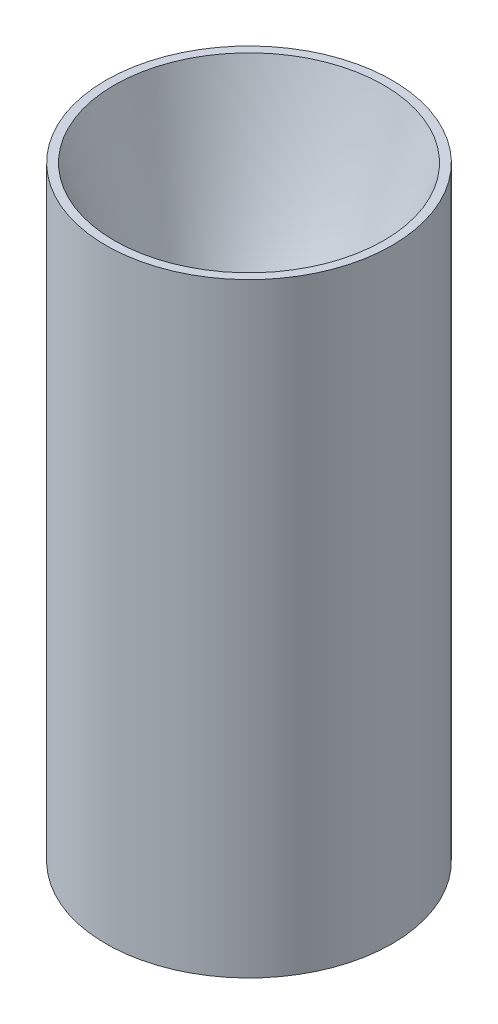
SolidWorks part; units mm, degrees
material "AISI 1020"
ref_plane "Front Plane" through (0, 0, 0) normal (0, 0, 1) x (1, 0, 0)
ref_plane "Top Plane" through (0, 0, 0) normal (0, 1, 0) x (1, 0, 0)
ref_plane "Right Plane" through (0, 0, 0) normal (1, 0, 0) x (0, 0, -1)
sketch "Sketch1" plane through (0, 0, 0) normal (0, 0, 1) x (1, 0, 0)
  line L0 (-0.0055, 165.816) -> (-0.0055, -134.6871) construction
  line L1 (71.7275, 109.9275) -> (76.1945, 109.9275)
  line L4 (53.8815, -59.7275) -> (53.8815, -212.1275)
  line L9 (76.1945, 109.9275) -> (76.1945, -212.1275)
  line L10 (76.1945, -212.1275) -> (53.8815, -212.1275)
  spline S0 degree 2 poles (26.7953, 6.5094) (49.2614, 34.6361) (71.7275, 109.9275) knots 0 0 0 1 1 1 construction
  spline S1 degree 2 poles (26.7953, 6.5094) (49.2614, 34.6361) (71.7275, 109.9275) knots 0 0 0 1 1 1
  spline S2 degree 4 poles (24.1269, -0.7179) (24.126, -0.7018) (24.1243, -0.6738) (24.121, -0.6546) (24.115, -0.5166) (24.1058, -0.4369) (24.0994, -0.1066) (24.0979, 0.0018) (24.102, 0.2678) (24.1085, 0.4272) (24.1205, 0.6469) (24.1414, 0.9016) (24.1752, 1.2027) (24.2265, 1.5422) (24.2905, 1.8812) (24.3671, 2.2165) (24.4563, 2.5494) (24.5577, 2.8783) (24.6716, 3.2035) (24.7972, 3.5238) (24.9353, 3.8398) (25.0841, 4.1494) (25.246, 4.4549) (25.4165, 4.7515) (25.6025, 5.0459) (25.7918, 5.3257) (26.0044, 5.6109) (26.1789, 5.8331) (26.3663, 6.0501) (26.5046, 6.2088) (26.757, 6.4728) (26.837, 6.5526) (27.1016, 6.806) (27.1881, 6.8783) (27.2854, 6.9667) (27.3038, 6.9803) (27.3264, 7.0004) knots 0 0 0 0 0 0.005192 0.010384 0.020768 0.041536 0.082569 0.102427 0.122284 0.142142 0.162 0.201716 0.241431 0.281147 0.320863 0.360578 0.400294 0.44001 0.479725 0.519441 0.559156 0.598872 0.638588 0.678303 0.718019 0.757735 0.79745 0.837166 0.857024 0.876882 0.916597 0.958047 0.979024 0.989512 1 1 1 1 1 construction
  spline S3 degree 4 poles (24.0991, 0.0002) (24.0991, 0.0361) (24.0996, 0.1103) (24.102, 0.2678) (24.1085, 0.4272) (24.1205, 0.6469) (24.1414, 0.9016) (24.1752, 1.2027) (24.2265, 1.5422) (24.2905, 1.8812) (24.3671, 2.2165) (24.4563, 2.5494) (24.5577, 2.8783) (24.6716, 3.2035) (24.7972, 3.5238) (24.9353, 3.8398) (25.0841, 4.1494) (25.246, 4.4549) (25.4165, 4.7515) (25.6025, 5.0459) (25.7918, 5.3257) (26.0044, 5.6109) (26.1789, 5.8331) (26.3663, 6.0501) (26.5046, 6.2088) (26.6704, 6.3823) (26.7445, 6.4586) (26.7953, 6.5094) knots 0.082569 0.082569 0.082569 0.082569 0.082569 0.102427 0.122284 0.142142 0.162 0.201716 0.241431 0.281147 0.320863 0.360578 0.400294 0.44001 0.479725 0.519441 0.559156 0.598872 0.638588 0.678303 0.718019 0.757735 0.79745 0.837166 0.857024 0.876882 0.916597 0.916597 0.916597 0.916597 0.916597
  spline S4 degree 4 poles (24.2082, 2.808) (24.2014, 2.7166) (24.1882, 2.5518) (24.1642, 2.1754) (24.1352, 1.6881) (24.1148, 1.1018) (24.103, 0.6556) (24.0988, 0.1104) (24.0988, -0.0999) (24.102, -0.543) (24.1083, -0.824) (24.1178, -1.1947) (24.1304, -1.5133) (24.1462, -1.8618) (24.1652, -2.1935) (24.1928, -2.6179) (24.2323, -3.1219) (24.3033, -3.8798) (24.4231, -4.8863) (24.5995, -6.0566) (24.8509, -7.385) (25.1518, -8.7034) (25.5018, -10.0095) (25.9004, -11.3017) (26.3469, -12.5779) (26.841, -13.8367) (27.3817, -15.076) (27.9685, -16.2944) (28.6001, -17.4898) (29.2765, -18.6611) (29.9954, -19.8056) (30.758, -20.9237) (31.4592, -21.8743) (32.0887, -22.6733) (32.6241, -23.3203) (33.0723, -23.8398) (33.5085, -24.3297) (33.9358, -24.7883) (34.2456, -25.1137) (34.6121, -25.4859) (34.7661, -25.6398) (35.1509, -26.0187) (35.4776, -26.3286) (35.905, -26.7273) (36.2395, -27.0242) (36.5192, -27.2707) (36.6465, -27.3798) (36.7148, -27.4387) (36.7496, -27.4686) knots 0 0 0 0 0 0.010393 0.020785 0.041571 0.062104 0.072371 0.082638 0.092575 0.102512 0.112449 0.122387 0.132324 0.142261 0.152198 0.162135 0.18201 0.201884 0.241633 0.281382 0.32113 0.360879 0.400628 0.440377 0.480126 0.519874 0.559623 0.599372 0.639121 0.67887 0.718618 0.758367 0.798116 0.81799 0.837865 0.857739 0.877613 0.897488 0.907425 0.917362 0.927629 0.937896 0.958429 0.979215 0.989607 0.994804 1 1 1 1 1 construction
  spline S5 degree 4 poles (24.0991, 0.0002) (24.0991, -0.0704) (24.0996, -0.2134) (24.102, -0.543) (24.1083, -0.824) (24.1178, -1.1947) (24.1304, -1.5133) (24.1462, -1.8618) (24.1652, -2.1935) (24.1928, -2.6179) (24.2323, -3.1219) (24.3033, -3.8798) (24.4231, -4.8863) (24.5995, -6.0566) (24.8509, -7.385) (25.1518, -8.7034) (25.5018, -10.0095) (25.9004, -11.3017) (26.3469, -12.5779) (26.841, -13.8367) (27.3817, -15.076) (27.9685, -16.2944) (28.6001, -17.4898) (29.2765, -18.6611) (29.9954, -19.8056) (30.758, -20.9237) (31.4592, -21.8743) (32.0887, -22.6733) (32.6241, -23.3203) (33.0723, -23.8398) (33.5085, -24.3297) (33.9358, -24.7883) (34.2456, -25.1137) (34.5369, -25.4095) (34.6364, -25.5098) (34.6863, -25.5597) knots 0.082638 0.082638 0.082638 0.082638 0.082638 0.092575 0.102512 0.112449 0.122387 0.132324 0.142261 0.152198 0.162135 0.18201 0.201884 0.241633 0.281382 0.32113 0.360879 0.400628 0.440377 0.480126 0.519874 0.559623 0.599372 0.639121 0.67887 0.718618 0.758367 0.798116 0.81799 0.837865 0.857739 0.877613 0.897488 0.907425 0.917362 0.917362 0.917362 0.917362 0.917362
  spline S6 degree 1 poles (34.6863, -25.5597) (43.2939, -34.1673) knots 0 0 1 1 construction
  spline S7 degree 1 poles (34.6863, -25.5597) (43.2939, -34.1673) knots 0 0 1 1
  spline S8 degree 4 poles (53.7724, -62.5352) (53.7792, -62.4464) (53.7924, -62.2737) (53.8104, -62.0016) (53.8309, -61.6599) (53.848, -61.2921) (53.8616, -60.9658) (53.8717, -60.5752) (53.8784, -60.2939) (53.8818, -59.8332) (53.8818, -59.6304) (53.8786, -59.1816) (53.8723, -58.9048) (53.8628, -58.5326) (53.8502, -58.2128) (53.8304, -57.7816) (53.8004, -57.281) (53.7562, -56.688) (53.6773, -55.8485) (53.5774, -55.0082) (53.4567, -54.1724) (53.2868, -53.1724) (53.0921, -52.1774) (52.8664, -51.1885) (52.61, -50.2075) (52.3293, -49.2331) (52.0243, -48.266) (51.6335, -47.1491) (51.1395, -45.8904) (50.5987, -44.651) (50.0121, -43.4327) (49.3801, -42.2371) (48.7041, -41.0662) (47.9845, -39.921) (47.2231, -38.8041) (46.5199, -37.8515) (45.8935, -37.0557) (45.3528, -36.4034) (44.9151, -35.8942) (44.5148, -35.447) (44.1815, -35.0846) (43.8739, -34.7603) (43.6741, -34.5515) (43.3653, -34.2383) (43.2159, -34.0889) (42.8277, -33.7066) (42.5041, -33.3998) (42.0741, -32.9986) (41.7412, -32.7033) (41.4607, -32.4559) (41.3338, -32.3472) (41.2653, -32.2883) (41.2305, -32.2583) knots 0 0 0 0 0 0.010393 0.020785 0.031178 0.041571 0.051838 0.062104 0.072371 0.082638 0.092575 0.102512 0.112449 0.122387 0.132324 0.142261 0.162135 0.18201 0.201884 0.241633 0.261507 0.281382 0.32113 0.360879 0.380754 0.400628 0.440377 0.480126 0.519874 0.559623 0.599372 0.639121 0.67887 0.718618 0.758367 0.798116 0.81799 0.837865 0.857739 0.877613 0.887551 0.897488 0.907425 0.917362 0.927629 0.937896 0.958429 0.979215 0.989607 0.994804 1 1 1 1 1 construction
  spline S9 degree 4 poles (53.8815, -59.7275) (53.8815, -59.657) (53.881, -59.5154) (53.8786, -59.1816) (53.8723, -58.9048) (53.8628, -58.5326) (53.8502, -58.2128) (53.8304, -57.7816) (53.8004, -57.281) (53.7562, -56.688) (53.6773, -55.8485) (53.5774, -55.0082) (53.4567, -54.1724) (53.2868, -53.1724) (53.0921, -52.1774) (52.8664, -51.1885) (52.61, -50.2075) (52.3293, -49.2331) (52.0243, -48.266) (51.6335, -47.1491) (51.1395, -45.8904) (50.5987, -44.651) (50.0121, -43.4327) (49.3801, -42.2371) (48.7041, -41.0662) (47.9845, -39.921) (47.2231, -38.8041) (46.5199, -37.8515) (45.8935, -37.0557) (45.3528, -36.4034) (44.9151, -35.8942) (44.5148, -35.447) (44.1815, -35.0846) (43.8739, -34.7603) (43.6741, -34.5515) (43.4444, -34.3185) (43.3438, -34.2172) (43.2939, -34.1673) knots 0.082638 0.082638 0.082638 0.082638 0.082638 0.092575 0.102512 0.112449 0.122387 0.132324 0.142261 0.162135 0.18201 0.201884 0.241633 0.261507 0.281382 0.32113 0.360879 0.380754 0.400628 0.440377 0.480126 0.519874 0.559623 0.599372 0.639121 0.67887 0.718618 0.758367 0.798116 0.81799 0.837865 0.857739 0.877613 0.887551 0.897488 0.907425 0.917362 0.917362 0.917362 0.917362 0.917362
  spline S10 degree 2 poles (36.8348, 6.4922) (58.6412, 42.997) (81.7275, 109.9275) knots 0.283015 0.283015 0.283015 0.999243 0.999243 0.999243 construction
  dimension "D1" = 24.1046
  dimension "D2" = 53.8871
  dimension "D3" = 152.4
  dimension "D4" = 322.055
  dimension "D5" = 152.4
  dimension "D7" = 24.0991
  dimension "D8" = 26.7953
  dimension "D9" = 34.6863
  dimension "D10" = 0.0002
revolve "Revolve2" add sketch "Sketch1" angle 360 about L0
sketch "Sketch2" plane through (0, -212.1275, 0) normal (0, -1, 0) x (1, 0, 0)
  line L1 (65.2, 0) -> (65.2, -54.0399) construction
  circle A3 centre (0, 0) radius 65.2 construction
  dimension "D1" = 130.4
hole_wizard "3/8-24 Tapped Hole1" positions "Sketch3" profile "Sketch4" tap size "3/8-24" standard "ANSI Inch"
sketch "Sketch3" plane through (0, -212.1275, 0) normal (0, -1, 0) x (-1, 0, 0)
  point P0 (-65.2, 0)
sketch "Sketch4" plane through (65.2, -212.1275, 0) normal (1, 0, 0) x (0, 0, -1)
  line L0 (0, 0) -> (0, 27.5335)
  line L1 (0, 27.5335) -> (4.2164, 25)
  line L2 (4.2164, 25) -> (4.2164, 0)
  line L5 (4.2164, 0) -> (0, 0)
  line L10 (0, 27.5335) -> (-4.2164, 25) construction
  line L11 (0, -6.35) -> (0, 107.95) construction
  dimension "Tap Drill Dia." = 8.4328
  dimension "Tap Drill Depth" = 25
  dimension "Drill Angle" = 118
cosmetic thread "Hole Thread1" parameters "D1"=20, "D2"=9.525
sketch "Sketch5" plane through (0, 0, 0) normal (0, 0, 1) x (1, 0, 0)
  line L0 (0, -228.487) -> (-0.0055, 109.9275) construction
  line L1 (71.7275, 109.9275) -> (-71.7386, 109.9275) construction
pattern_circular "CirPattern1" count 8 over 360 about axis through (0, -228.487, 0) along (0, 1, 0) of "3/8-24 Tapped Hole1"
cosmetic thread "Hole Thread2" parameters "D1"=20, "D2"=9.525
cosmetic thread "Hole Thread3" parameters "D1"=20, "D2"=9.525
cosmetic thread "Hole Thread4" parameters "D1"=20, "D2"=9.525
cosmetic thread "Hole Thread5" parameters "D1"=20, "D2"=9.525
cosmetic thread "Hole Thread6" parameters "D1"=20, "D2"=9.525
cosmetic thread "Hole Thread7" parameters "D1"=20, "D2"=9.525
cosmetic thread "Hole Thread8" parameters "D1"=20, "D2"=9.525
sketch "Sketch8" plane through (0, -212.1275, 0) normal (0, -1, 0) x (1, 0, 0)
  circle A0 centre (0, 0) radius 53.8815 construction
  circle A1 centre (0, 0) radius 76.49 construction
  circle A2 centre (0, 0) radius 65.2002 construction
  dimension "D1" = 107.7631
  dimension "D2" = 130.4004
  dimension "D3" = 152.98
sketch "Sketch9" plane through (0, -212.1275, 0) normal (0, -1, 0) x (1, 0, 0)
  circle A0 centre (0, 0) radius 53.8815
  circle A1 centre (0, 0) radius 56.8815
  dimension "D1" = 3
extrude "Cut-Extrude1" [suppressed] cut sketch "Sketch9" against normal blind 6
hole_wizard "1/4 (0.2500) Dowel Hole1" positions "Sketch11" profile "Sketch12" hole size "1/4" standard "ANSI Inch"
sketch "Sketch11" plane through (0, -212.1275, 0) normal (0, -1, 0) x (-1, 0, 0)
  line L1 (46.1046, -46.1039) -> (65.2014, 0) construction
  line L3 (-65.2, 0) -> (-46.1032, 46.1039) construction
  line L4 (-46.1032, 46.1038) -> (-46.1033, 46.1036) construction
  line L6 (0, 0) -> (60.2371, -24.9507) construction
  line L8 (0, 0) -> (-60.2368, 24.9512) construction
  circle A0 centre (0, 0) radius 65.2 construction
  point P22 (60.2371, -24.9507)
  point P25 (55.653, -23.0519)
  point P28 (-60.2368, 24.9512)
  point P32 (-55.6516, 23.0519)
sketch "Sketch12" plane through (60.2368, -212.1275, -24.9512) normal (1, 0, 0) x (0, 0, -1)
  line L0 (0, 0) -> (0, 11.8137)
  line L1 (0, 11.8137) -> (3.175, 9.906)
  line L2 (3.175, 9.906) -> (3.175, 0)
  line L5 (3.175, 0) -> (0, 0)
  line L10 (0, 11.8137) -> (-3.175, 9.906) construction
  line L11 (0, -6.35) -> (0, 107.95) construction
  dimension "Hole Dia." = 6.35
  dimension "Hole Depth" = 9.906
  dimension "Drill Angle" = 118
